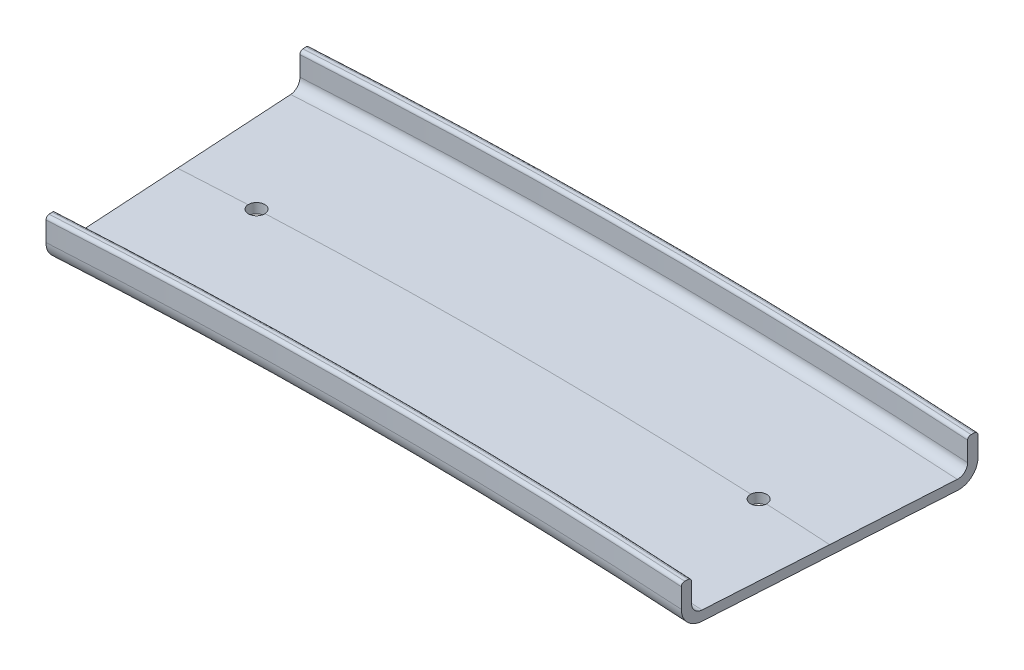
SolidWorks part; units mm, degrees
ref_plane "Front Plane" through (0, 0, 0) normal (0, 0, 1) x (1, 0, 0)
ref_plane "Top Plane" through (0, 0, 0) normal (0, 1, 0) x (1, 0, 0)
ref_plane "Right Plane" through (0, 0, 0) normal (1, 0, 0) x (0, 0, -1)
sketch "Sketch1" plane through (0, 0, 0) normal (1, 0, 0) x (0, 0, -1)
  line L0 (0, 0) -> (-37, 0)
  line L1 (-40, 3) -> (-40, 9)
  line L2 (-41, 10) -> (-42, 10)
  line L3 (-43, 9) -> (-43, 3)
  line L4 (-37, -3) -> (37, -3)
  line L5 (43, 3) -> (43, 9)
  line L6 (42, 10) -> (41, 10)
  line L7 (40, 9) -> (40, 3)
  line L8 (37, 0) -> (0, 0)
  arc A0 (40, 3) -> (37, 0) centre (37, 3) cw
  arc A1 (-37, 0) -> (-40, 3) centre (-37, 3) cw
  arc A2 (37, -3) -> (43, 3) centre (37, 3) ccw
  arc A3 (-43, 3) -> (-37, -3) centre (-37, 3) ccw
  arc A4 (43, 9) -> (42, 10) centre (42, 9) ccw
  arc A5 (41, 10) -> (40, 9) centre (41, 9) ccw
  arc A6 (-40, 9) -> (-41, 10) centre (-41, 9) ccw
  arc A7 (-42, 10) -> (-43, 9) centre (-42, 9) ccw
  point P14 (-40, 0)
  point P21 (43, 10)
  point P24 (40, 10)
  point P27 (-40, 10)
  dimension "D5" = 3
  dimension "D6" = 6
  dimension "D7" = 1
  dimension "D1" = 80
  dimension "D2" = 10
  dimension "D3" = 3
  dimension "D4" = 3
sketch "Sketch2" plane through (0, 0, 0) normal (0, 1, 0) x (1, 0, 0)
  arc A0 (-100, -3) -> (100, -3) centre (0, -1668.1667) cw
  point P3 (0, 0)
  point P5 (0, 0)
  dimension "D1" = 3
  dimension "D2" = 200
sweep "Ceiling structural member cradle" add profiles "Sketch1" path "Sketch2"
sketch "Sketch3" plane through (0, 0, 0) normal (0, 1, 0) x (1, 0, 0)
  circle A0 centre (-77, -1.778) radius 2.5
  arc A1 (100, -3) -> (-100, -3) centre (0, -1668.1667) ccw construction
  circle A2 centre (77, -1.778) radius 2.5
  arc A3 (100, -3) -> (-100, -3) centre (0, -1668.1667) ccw construction
  point P10 (0, 0)
  dimension "D1" = 5
  dimension "D2" = 77
  dimension "D3" = 77
extrude "Retaining screw holes" cut sketch "Sketch3" against normal through all both and the other way through all
sketch "Reference 1 for display plane" plane through (0, 0, 0) normal (0, 1, 0) x (1, 0, 0)
  line L1 (0, 0) -> (-28.1908, 10.2606)
  line L2 (74.5026, -1.6645) -> (-74.5026, -1.6645)
  line L3 (-77, -1.778) -> (16.9693, -35.9801)
  arc A0 (-79.4972, -1.8953) -> (-74.5026, -1.6645) centre (-77, -1.778) ccw construction
  arc A1 (-74.5026, -1.6645) -> (-79.4972, -1.8953) centre (-77, -1.778) ccw construction
  arc A2 (-79.4972, -1.8953) -> (-74.5026, -1.6645) centre (-77, -1.778) ccw
  arc A3 (-74.5026, -1.6645) -> (-79.4972, -1.8953) centre (-77, -1.778) ccw
  point P16 (-76.8576, -2.1953)
  dimension "D1" = 20
  dimension "D2" = 30
  dimension "D3" = 100
ref_plane "Reference plane 1 for display plane" through (-9.5787, 0, 26.3174) normal (-0.342, 0, 0.9397) x (0.9397, 0, 0.342)
ref_plane "Display plane (before offset)" through (-8.4582, -9.0011, 23.2388) normal (-0.3214, -0.342, 0.883) x (0.9397, 0, 0.342)
ref_plane "Actual display plane (offset)" through (-16.4931, -17.5516, 45.3144) normal (-0.3214, -0.342, 0.883) x (0.9397, 0, 0.342)
sketch "Alignment sketch" plane through (-16.4931, -17.5516, 45.3144) normal (-0.3214, -0.342, 0.883) x (0.9397, 0, 0.342)
  line L1 (-84.5236, 10) -> (115.4764, 10)
  line L2 (-84.5236, 10) -> (-84.5236, -100)
  line L3 (-84.5236, -100) -> (115.4764, -100)
  line L4 (115.4764, 10) -> (115.4764, -100)
  line L5 (105.5431, -1.423) -> (84.4476, -25.6823) construction
  line L6 (15.4764, 10) -> (15.4764, -100)
  line L7 (-84.5236, -45) -> (115.4764, -45)
  dimension "D1" = 200
  dimension "D2" = 110
  dimension "D3" = 10
